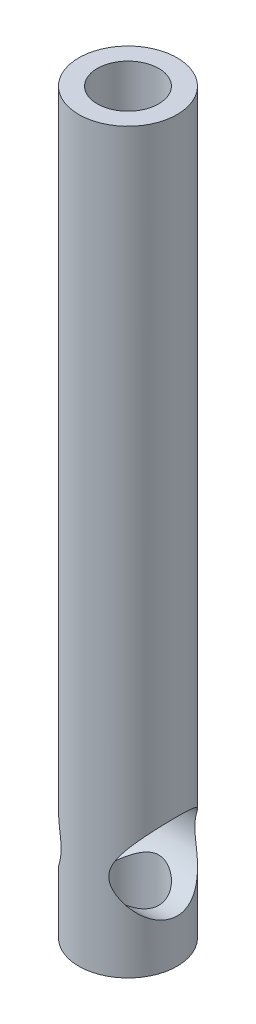
SolidWorks part; units mm, degrees
ref_plane "Front Plane" through (0, 0, 0) normal (0, 0, 1) x (1, 0, 0)
ref_plane "Top Plane" through (0, 0, 0) normal (0, 1, 0) x (1, 0, 0)
ref_plane "Right Plane" through (0, 0, 0) normal (1, 0, 0) x (0, 0, -1)
sketch "Sketch1" plane through (0, 0, 0) normal (0, 1, 0) x (1, 0, 0)
  circle A0 centre (0, 0) radius 12.5
  circle A1 centre (0, 0) radius 20
  dimension "D1" = 25
  dimension "D2" = 40
extrude "Boss-Extrude1" add sketch "Sketch1" along normal blind 300
ref_plane "Plane1" through (0, 0, 0) normal (1, 0, 0) x (0, 0, -1)
sketch "Sketch2" plane through (0, 0, 0) normal (1, 0, 0) x (0, 0, -1)
  line L0 (0, 0) -> (0, 35.2171) construction
  line L1 (0, 35.2171) -> (20, 35.2171) construction
  line L2 (20, 0) -> (20, 300) construction
  circle A0 centre (0, 35.2171) radius 17.5
  dimension "D1" = 35
extrude "Cut-Extrude1" cut sketch "Sketch2" against normal up to surface and the other way up to surface contours A0 up to face at (0, 300, 20) other way up to face at (0, 300, 20)
